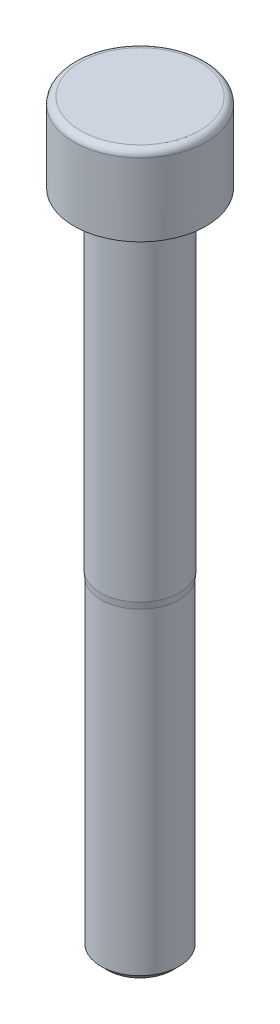
SolidWorks part; units mm, degrees
ref_plane "Plan de face" through (0, 0, 0) normal (0, 0, 1) x (1, 0, 0)
ref_plane "Plan de dessus" through (0, 0, 0) normal (0, 1, 0) x (1, 0, 0)
ref_plane "Plan de droite" through (0, 0, 0) normal (1, 0, 0) x (0, 0, -1)
sketch "Esquisse1" plane through (0, 0, 0) normal (0, 0, 1) x (1, 0, 0)
  line L0 (0, 0) -> (0, 56) construction
  line L1 (0, 56) -> (5, 56)
  line L2 (5, 56) -> (5, 50)
  line L3 (5, 50) -> (3, 50)
  line L4 (3, 50) -> (3, 25)
  line L5 (3, 25) -> (2.95, 24.5)
  line L6 (2.95, 24.5) -> (2.95, 0)
  line L7 (2.95, 0) -> (0, 0)
  line L8 (0, 0) -> (0, 56)
  point P3 (2.95, 12.7481)
  point P10 (9.7673, 55.3338)
  dimension "D1" = 5.9
  dimension "D2" = 6
  dimension "D3" = 0.5
  dimension "D4" = 25
  dimension "D5" = 50
  dimension "D6" = 6
  dimension "D7" = 10
revolve "Révolution1" add sketch "Esquisse1" angle 360 about L0
chamfer "Chanfrein1" distance 0.5 angle 45 1 edges at (0, 0, -2.95)
fillet "Congé1" radius 0.5 1 edges at (0, 56, -5)
